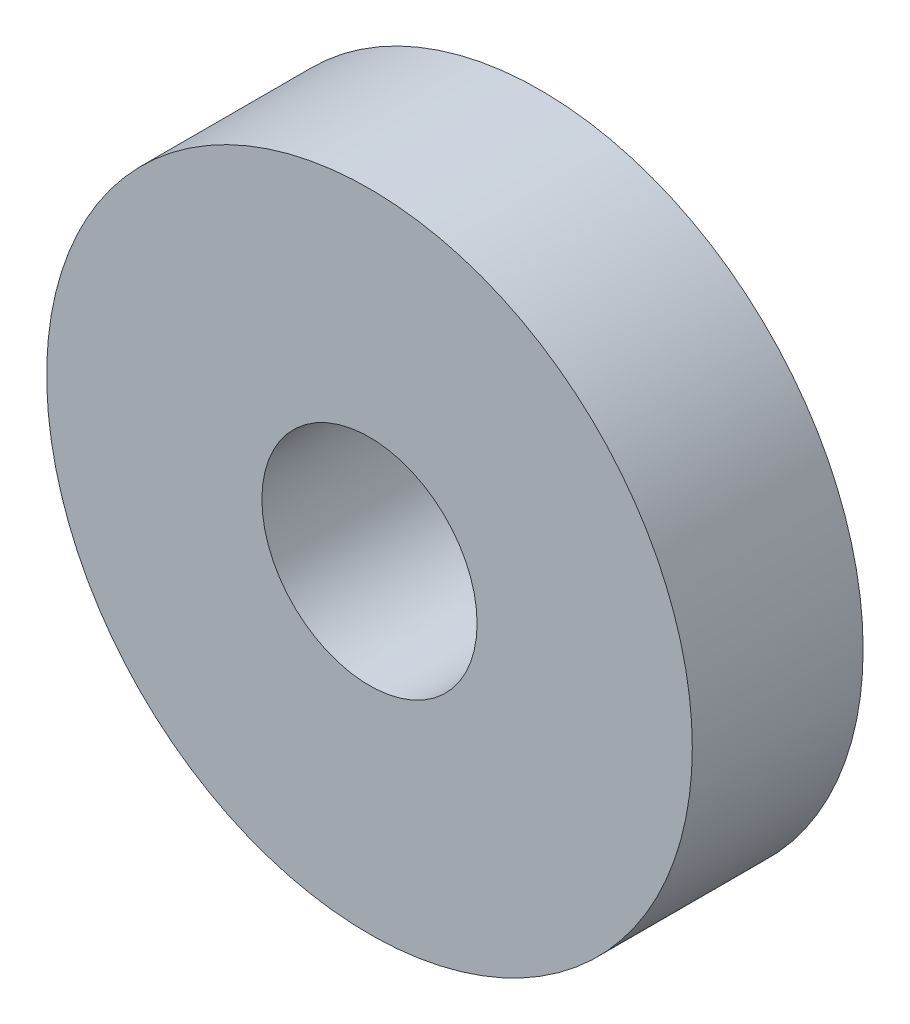
SolidWorks part; units mm, degrees
ref_plane "Front Plane" through (0, 0, 0) normal (0, 0, 1) x (1, 0, 0)
ref_plane "Top Plane" through (0, 0, 0) normal (0, 1, 0) x (1, 0, 0)
ref_plane "Right Plane" through (0, 0, 0) normal (1, 0, 0) x (0, 0, -1)
sketch "Sketch1" plane through (0, 0, 0) normal (0, 0, 1) x (1, 0, 0)
  circle A0 centre (0, 0) radius 6
  circle A1 centre (0, 0) radius 2
  dimension "D1" = 4
  dimension "D2" = 12
extrude "Boss-Extrude1" add sketch "Sketch1" along normal blind 3.175
